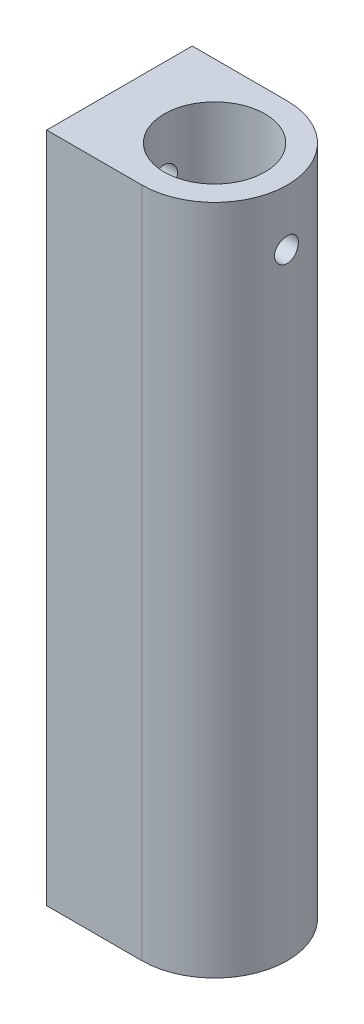
SolidWorks part; units mm, degrees
ref_plane "Front Plane" through (0, 0, 0) normal (0, 0, 1) x (1, 0, 0)
ref_plane "Top Plane" through (0, 0, 0) normal (0, 1, 0) x (1, 0, 0)
ref_plane "Right Plane" through (0, 0, 0) normal (1, 0, 0) x (0, 0, -1)
sketch "Sketch1" plane through (0, 0, 0) normal (0, 1, 0) x (1, 0, 0)
  line L0 (0, 8.255) -> (-10.795, 8.255)
  line L1 (-10.795, 8.255) -> (-10.795, -8.255)
  line L2 (-10.795, -8.255) -> (0, -8.255)
  line L3 (-5.715, 0) -> (-5.715, -8.255) construction
  circle A0 centre (0, 0) radius 5.715
  arc A1 (0, -8.255) -> (0, 8.255) centre (0, 0) ccw
  dimension "D1" = 11.43
  dimension "D2" = 16.51
  dimension "D3" = 5.08
extrude "Boss-Extrude1" add sketch "Sketch1" along normal blind 76.2
sketch "Sketch4" plane through (0, 0, 0) normal (0, -1, 0) x (1, 0, 0)
  circle A0 centre (0, 0) radius 5.715
  circle A1 centre (0, 0) radius 5.207
  circle A2 centre (0, 0) radius 5.715 construction
  dimension "D1" = 10.414
extrude "Boss-Extrude2" add sketch "Sketch4" against normal blind 3.81
hole_wizard "#6-32 Tapped Hole1" positions "Sketch5" profile "Sketch6" tap size "#6-32" standard "ANSI Inch" end condition through all
sketch "Sketch5" plane through (-10.795, 0, 0) normal (-1, 0, 0) x (0, 0, 1)
  line L0 (-8.255, 76.2) -> (8.255, 76.2) construction
  line L1 (8.255, 76.2) -> (8.255, 0) construction
  line L2 (0, 76.2) -> (0, 95.631) construction
  point P0 (0, 69.85)
  dimension "D1" = 6.35
  dimension "D2" = 8.255
sketch "Sketch6" plane through (-10.795, 69.85, 0) normal (0, 1, 0) x (0, 0, 1)
  line L0 (0, 0) -> (0, 19.05)
  line L1 (0, 19.05) -> (1.3525, 19.05)
  line L2 (1.3525, 19.05) -> (1.3525, 0)
  line L5 (1.3525, 0) -> (0, 0)
  line L11 (0, -6.35) -> (0, 107.95) construction
  dimension "Thru Tap Drill Dia." = 2.7051
  dimension "Thru Tap Drill Depth" = 19.05
cosmetic thread "Hole Thread1" parameters "D2"=3.5052
